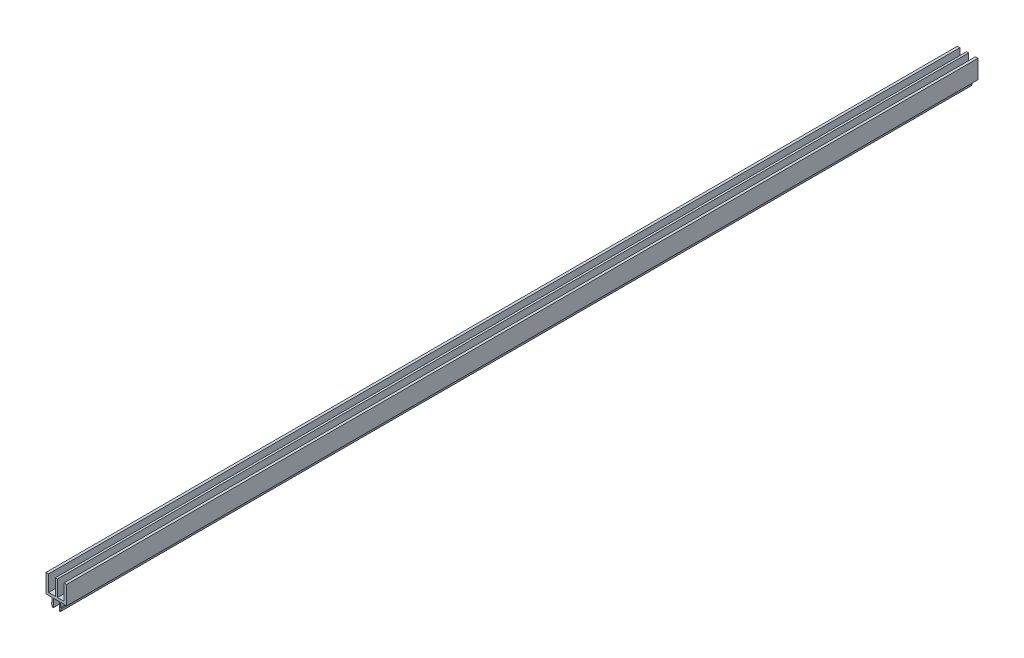
SolidWorks part; units mm, degrees
ref_plane "Plan de face" through (0, 0, 0) normal (0, 0, 1) x (1, 0, 0)
ref_plane "Plan de dessus" through (0, 0, 0) normal (0, 1, 0) x (1, 0, 0)
ref_plane "Plan de droite" through (0, 0, 0) normal (1, 0, 0) x (0, 0, -1)
ref_plane "Plan1" through (0, 0, 50) normal (0, 0, 1) x (1, 0, 0)
sketch "Esquisse1" plane through (0, 0, 50) normal (0, 0, 1) x (1, 0, 0)
  line L0 (-1, 2.5) -> (-7.5, 2.5)
  line L1 (-7.5, 2.5) -> (-7.5, 18)
  line L2 (-7.5, 18) -> (-10, 18)
  line L3 (-10, 18) -> (-10, 0)
  line L4 (-10, 0) -> (-4, 0)
  line L5 (-4, 0) -> (-4, -4.5)
  line L6 (-4, -4.5) -> (-5, -4.5)
  line L7 (-5, -4.5) -> (-3.75, -8)
  line L8 (-3.75, -8) -> (-3, -8)
  line L9 (-3, -8) -> (-3, 0)
  line L10 (-3, 0) -> (3, 0)
  line L11 (3, 0) -> (3, -8)
  line L12 (3, -8) -> (3.75, -8)
  line L13 (3.75, -8) -> (5, -4.5)
  line L14 (5, -4.5) -> (4, -4.5)
  line L15 (4, -4.5) -> (4, 0)
  line L16 (4, 0) -> (10, 0)
  line L17 (10, 0) -> (10, 18)
  line L18 (10, 18) -> (7.5, 18)
  line L19 (7.5, 18) -> (7.5, 2.5)
  line L20 (7.5, 2.5) -> (1, 2.5)
  line L21 (1, 2.5) -> (1, 18)
  line L22 (1, 18) -> (-1, 18)
  line L23 (-1, 18) -> (-1, 2.5)
extrude "Boss.-Extru.1" add sketch "Esquisse1" against normal blind 879
